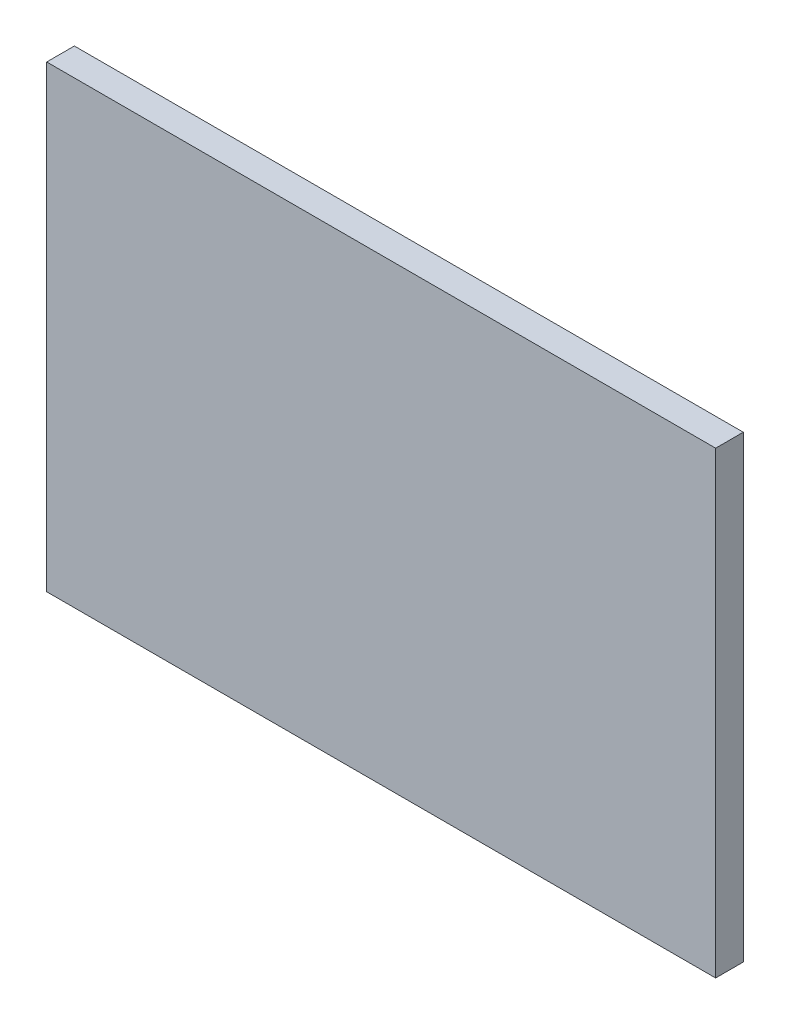
SolidWorks part; units mm, degrees
ref_plane "Front Plane" through (0, 0, 0) normal (0, 0, 1) x (1, 0, 0)
ref_plane "Top Plane" through (0, 0, 0) normal (0, 1, 0) x (1, 0, 0)
ref_plane "Right Plane" through (0, 0, 0) normal (1, 0, 0) x (0, 0, -1)
sketch "Sketch1" plane through (0, 0, 0) normal (0, 0, 1) x (1, 0, 0)
  line L1 (-45.7985, 34.4338) -> (75.2015, 34.4338)
  line L2 (-45.7985, 34.4338) -> (-45.7985, -48.5662)
  line L3 (-45.7985, -48.5662) -> (75.2015, -48.5662)
  line L4 (75.2015, 34.4338) -> (75.2015, -48.5662)
  dimension "D1" = 121
  dimension "D2" = 83
extrude "Boss-Extrude1" add sketch "Sketch1" along normal blind 5
